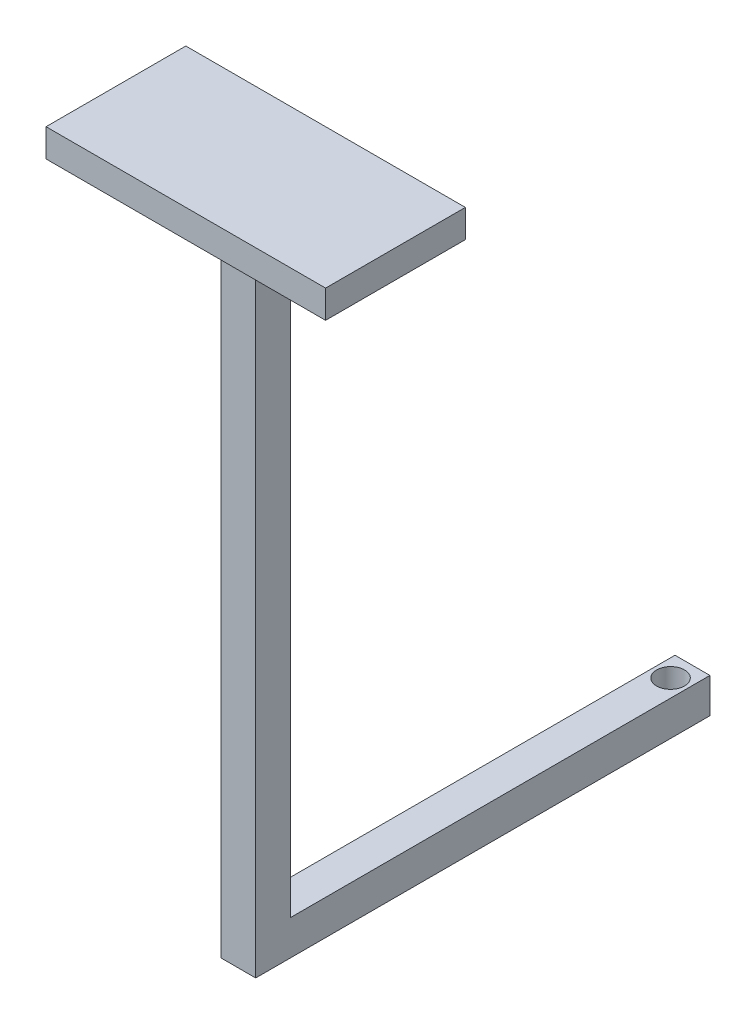
SolidWorks part; units mm, degrees
ref_plane "Plan de face" through (0, 0, 0) normal (0, 0, 1) x (1, 0, 0)
ref_plane "Plan de dessus" through (0, 0, 0) normal (0, 1, 0) x (1, 0, 0)
ref_plane "Plan de droite" through (0, 0, 0) normal (1, 0, 0) x (0, 0, -1)
sketch "Esquisse1" plane through (0, 0, 0) normal (0, 1, 0) x (1, 0, 0)
  line L1 (-100, -50) -> (100, -50)
  line L2 (-100, -50) -> (-100, 50)
  line L3 (-100, 50) -> (100, 50)
  line L4 (100, -50) -> (100, 50)
  line L5 (-100, -50) -> (100, 50) construction
  line L6 (-100, 50) -> (100, -50) construction
  point P0 (0, 0)
  dimension "D1" = 200
  dimension "D2" = 100
extrude "Boss.-Extru.1" add sketch "Esquisse1" along normal blind 20
sketch "Esquisse2" plane through (0, 0, 0) normal (0, 1, 0) x (1, 0, 0)
  line L1 (-12.5, -12.5) -> (12.5, -12.5)
  line L2 (-12.5, -12.5) -> (-12.5, 12.5)
  line L3 (-12.5, 12.5) -> (12.5, 12.5)
  line L4 (12.5, -12.5) -> (12.5, 12.5)
  line L5 (-12.5, -12.5) -> (12.5, 12.5) construction
  line L6 (-12.5, 12.5) -> (12.5, -12.5) construction
  point P0 (0, 0)
  dimension "D1" = 25
  dimension "D2" = 25
extrude "Boss.-Extru.2" add sketch "Esquisse2" against normal blind 470
ref_plane "Plan2" through (0, 0, -12.5) normal (0, 0, -1) x (-1, 0, 0)
sketch "Esquisse6" plane through (0, 0, -12.5) normal (0, 0, -1) x (-1, 0, 0)
  line L0 (12.5, -470) -> (12.5, 0) construction
  line L1 (-12.5, -470) -> (12.5, -470)
  line L2 (-12.5, -470) -> (-12.5, -445)
  line L3 (-12.5, -445) -> (12.5, -445)
  line L4 (12.5, -470) -> (12.5, -445)
  line L5 (-12.5, -470) -> (12.5, -470) construction
  dimension "D1" = 25
  dimension "D2" = 25
extrude "Boss.-Extru.3" add sketch "Esquisse6" along normal blind 300
sketch "Esquisse9" plane through (0, -445, 0) normal (0, 1, 0) x (1, 0, 0)
  circle A0 centre (0, 296.8284) radius 10
extrude "Enlèv. mat.-Extru.1" cut sketch "Esquisse9" against normal blind 30
